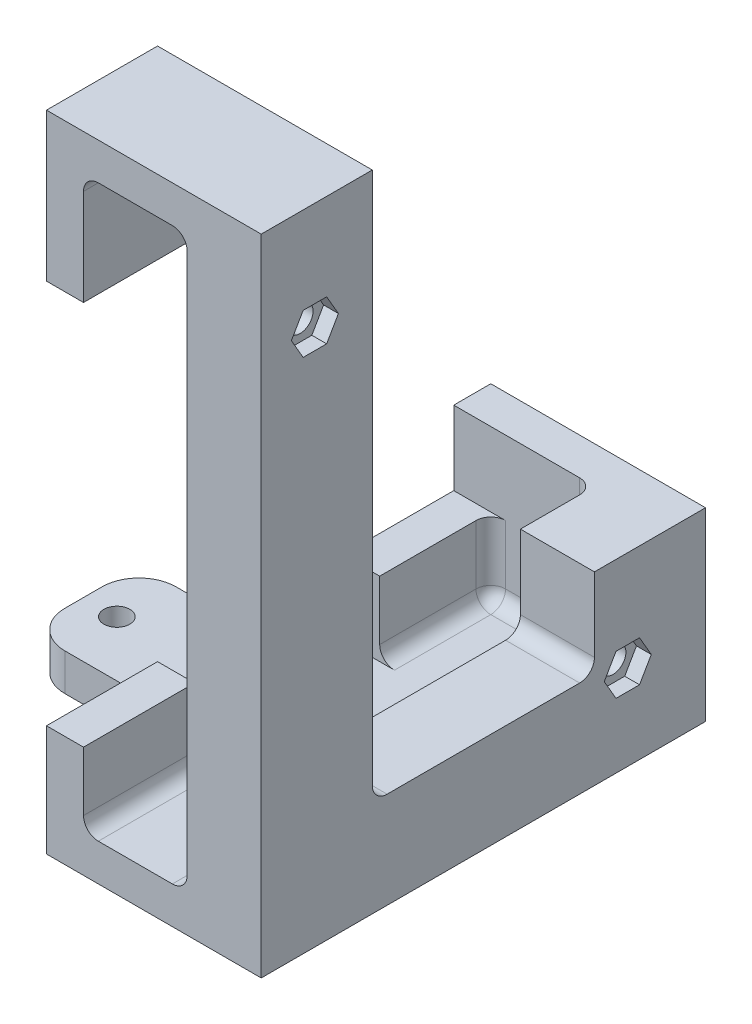
SolidWorks part; units mm, degrees
material "ABS"
ref_plane "Front Plane" through (0, 0, 0) normal (0, 0, 1) x (1, 0, 0)
ref_plane "Top Plane" through (0, 0, 0) normal (0, 1, 0) x (1, 0, 0)
ref_plane "Right Plane" through (0, 0, 0) normal (1, 0, 0) x (0, 0, -1)
sketch "Sketch1" plane through (0, 0, 0) normal (0, 0, 1) x (1, 0, 0)
  line L0 (-50.0169, 0) -> (66.8865, 0) construction
  line L1 (0, 0) -> (0, 87)
  line L2 (0, 87) -> (-24, 87)
  line L3 (-24, 87) -> (-24, 67)
  line L4 (-24, 67) -> (-19, 67)
  line L5 (-19, 67) -> (-19, 80)
  line L6 (-17, 82) -> (-7, 82)
  line L7 (-5, 80) -> (-5, 75.9133)
  line L8 (-5, 75.9133) -> (-5, 0)
  line L9 (-5, 0) -> (0, 0)
  arc A0 (-7, 82) -> (-5, 80) centre (-7, 80) cw
  arc A1 (-19, 80) -> (-17, 82) centre (-17, 80) cw
  point P15 (-5, 82)
  point P18 (-19, 82)
  dimension "D7" = 2
  dimension "D1" = 14
  dimension "D2" = 5
  dimension "D3" = 5
  dimension "D4" = 82
  dimension "D5" = 5
  dimension "D6" = 15
extrude "Boss-Extrude1" add sketch "Sketch1" against normal blind 15
sketch "Sketch2" plane through (0, 0, 0) normal (0, 0, 1) x (1, 0, 0)
  line L0 (-5, 0) -> (-24, 0)
  line L1 (-24, 0) -> (-24, 0.8525)
  line L2 (-24, 0.8525) -> (-24, 15)
  line L3 (-24, 15) -> (-19, 15)
  line L4 (-19, 15) -> (-19, 5)
  line L5 (-19, 5) -> (-5, 5)
  line L6 (-5, 80) -> (-5, 0) construction
  line L8 (-5, 5) -> (-5, 25)
  line L9 (-5, 25) -> (0, 25)
  line L10 (0, 0) -> (0, 87) construction
  line L11 (0, 25) -> (0, 0)
  line L12 (0, 0) -> (-5, 0)
  dimension "D1" = 14
  dimension "D2" = 5
  dimension "D3" = 5
  dimension "D4" = 15
  dimension "D5" = 25
extrude "Boss-Extrude2" add sketch "Sketch2" against normal blind 60
sketch "Sketch3" plane through (0, 0, -60) normal (0, 0, -1) x (-1, 0, 0)
  line L0 (0, 25) -> (24, 25)
  line L1 (0, 25) -> (0, 0)
  line L2 (24, 25) -> (24, 0)
  line L3 (0, 0) -> (24, 0)
  line L4 (24, 15) -> (24, 0) construction
extrude "Boss-Extrude3" add sketch "Sketch3" against normal blind 5
fillet "Fillet1" radius 2 2 edges at (-5, 5, -27.5) (-19, 5, -27.5)
sketch "Sketch4" plane through (-24, 0, 0) normal (-1, 0, 0) x (0, 0, 1)
  line L0 (-55, 15) -> (-55, 5)
  line L1 (-55, 5) -> (-15, 5)
  line L2 (-15, 5) -> (-15, 15)
  line L3 (-55, 15) -> (0, 15) construction
  line L4 (-60, 0) -> (0, 0) construction
  dimension "D1" = 5
extrude "Cut-Extrude1" cut sketch "Sketch4" against normal blind 9 and the other way through all
sketch "Sketch5" plane through (-5, 0, 0) normal (-1, 0, 0) x (0, 0, 1)
  line L0 (-45, 25) -> (-45, 13)
  line L1 (-45, 25) -> (-15, 25)
  line L2 (-45, 13) -> (-15, 13)
  line L4 (-55, 25) -> (-15, 25) construction
  line L5 (-55, 25) -> (-55, 7) construction
  line L6 (-15, 25) -> (-15, 13)
  dimension "D1" = 12
  dimension "D2" = 10
extrude "Cut-Extrude2" cut sketch "Sketch5" against normal blind 9
fillet "Fillet2" radius 2 3 edges at (-5, 16, -55) (-5.5858, 5.5858, -55) (-15.5, 5, -55)
fillet "Fillet3" radius 2 1 edges at (-2.5, 13, -45)
fillet "Fillet4" radius 2 1 edges at (-2.5, 13, -15)
sketch "Sketch6" plane through (-24, 0, 0) normal (-1, 0, 0) x (0, 0, 1)
  line L0 (-55, 5) -> (-55, 15)
  line L1 (-55, 5) -> (-40, 5)
  line L2 (-55, 15) -> (-40, 15)
  line L3 (-40, 5) -> (-40, 15)
  line L4 (-55, 7) -> (-55, 25) construction
  line L5 (-15, 15) -> (0, 15) construction
  line L6 (-53, 5) -> (-15, 5) construction
extrude "Boss-Extrude4" add sketch "Sketch6" against normal blind 5
fillet "Fillet5" radius 2 3 edges at (-19, 11, -55) (-19, 5.5858, -54.4142) (-19, 5, -46.5)
sketch "Sketch10" plane through (0, 0, 0) normal (1, 0, 0) x (0, 0, -1)
  line L8 (43, 13) -> (17, 13)
  line L9 (15, 15) -> (15, 87)
  line L10 (15, 87) -> (0, 87)
  line L11 (0, 87) -> (0, 0)
  line L12 (0, 0) -> (60, 0)
  line L13 (60, 0) -> (60, 25)
  line L14 (60, 25) -> (45, 25)
  line L15 (45, 25) -> (45, 15)
  line L16 (43, 13) -> (17, 13)
  line L17 (15, 15) -> (15, 87)
  line L18 (15, 87) -> (0, 87)
  line L19 (0, 87) -> (0, 0)
  line L20 (0, 0) -> (60, 0)
  line L21 (60, 0) -> (60, 25)
  line L22 (60, 25) -> (45, 25)
  line L23 (45, 25) -> (45, 15)
  arc A2 (15, 15) -> (17, 13) centre (17, 15) ccw
  arc A3 (43, 13) -> (45, 15) centre (43, 15) ccw
  arc A4 (15, 15) -> (17, 13) centre (17, 15) ccw
  arc A5 (43, 13) -> (45, 15) centre (43, 15) ccw
  dimension "D1" = 0
extrude "Boss-Extrude6" add sketch "Sketch10" along normal blind 5
sketch "Sketch11" plane through (5, 0, 0) normal (1, 0, 0) x (0, 0, -1)
  line L0 (15, 87) -> (0, 87) construction
  line L1 (15, 15) -> (15, 87) construction
  line L2 (60, 0) -> (60, 25) construction
  line L3 (0, 0) -> (60, 0) construction
  circle A0 centre (49.5, 11.5) radius 1.75
  circle A1 centre (7.2484, 72.5) radius 1.75
  dimension "D1" = 3.5
  dimension "D2" = 14.5
  dimension "D3" = 7.7516
  dimension "D4" = 10.5
  dimension "D5" = 3.5
  dimension "D6" = 11.5
extrude "Cut-Extrude6" cut sketch "Sketch11" against normal blind 17
sketch "Sketch14" plane through (5, 0, 0) normal (1, 0, 0) x (0, 0, -1)
  line L1 (10.4238, 72.5) -> (8.8361, 75.25)
  line L2 (8.8361, 75.25) -> (5.6607, 75.25)
  line L3 (5.6607, 75.25) -> (4.073, 72.5)
  line L4 (4.073, 72.5) -> (5.6607, 69.75)
  line L5 (5.6607, 69.75) -> (8.8361, 69.75)
  line L6 (8.8361, 69.75) -> (10.4238, 72.5)
  line L7 (52.6754, 11.5) -> (51.0877, 14.25)
  line L8 (51.0877, 14.25) -> (47.9123, 14.25)
  line L9 (47.9123, 14.25) -> (46.3246, 11.5)
  line L10 (46.3246, 11.5) -> (47.9123, 8.75)
  line L11 (47.9123, 8.75) -> (51.0877, 8.75)
  line L12 (51.0877, 8.75) -> (52.6754, 11.5)
  circle A2 centre (7.2484, 72.5) radius 2.75 construction
  circle A3 centre (49.5, 11.5) radius 2.75 construction
  dimension "D1" = 5.5
  dimension "D2" = 5.5
extrude "Cut-Extrude7" cut sketch "Sketch14" against normal blind 2
sketch "Sketch16" plane through (0, 0, 0) normal (0, 1, 0) x (1, 0, 0)
  line L0 (-24, 27.5) -> (-55.3719, 27.5) construction
  line L1 (-24, 40) -> (-24, 15) construction
  line L2 (-24, 35) -> (-41.5, 35)
  line L3 (-46.5, 30) -> (-46.5, 25)
  line L4 (-41.5, 20) -> (-24, 20)
  line L5 (-24, 35) -> (-24, 20)
  line L6 (-7, 0) -> (-17, 0) construction
  arc A0 (-46.5, 25) -> (-41.5, 20) centre (-41.5, 25) ccw
  arc A1 (-41.5, 35) -> (-46.5, 30) centre (-41.5, 30) ccw
  circle A2 centre (-42, 27.5) radius 1.75
  point P12 (-46.5, 35)
  point P17 (-12, 0)
  dimension "D4" = 5
  dimension "D5" = 3.5
  dimension "D6" = 30
  dimension "D1" = 22.5
  dimension "D2" = 7.5
  dimension "D3" = 7.5
extrude "Boss-Extrude7" add sketch "Sketch16" along normal up to surface (5 mm away) up to face at (-16.25, 5, -27)
sketch "Sketch17" plane through (0, 0, 0) normal (0, -1, 0) x (1, 0, 0)
  line L0 (-9.5, 0) -> (-9.5, -60) construction
  line L1 (-24, 0) -> (5, 0) construction
  line L2 (-24, -60) -> (5, -60) construction
  line L4 (-12, -12.5) -> (-7, -12.5)
  line L5 (-12, -12.5) -> (-12, -47.5)
  line L6 (-12, -47.5) -> (-7, -47.5)
  line L7 (-7, -12.5) -> (-7, -47.5)
  line L8 (-12, -12.5) -> (-7, -47.5) construction
  line L9 (-12, -47.5) -> (-7, -12.5) construction
  point P6 (-9.5, -30)
  dimension "D1" = 5
  dimension "D2" = 35
extrude "Boss-Extrude8" add sketch "Sketch17" along normal blind 10
fillet "Fillet6" radius 2 2 edges at (-9.5, -10, -47.5) (-9.5, -10, -12.5)
